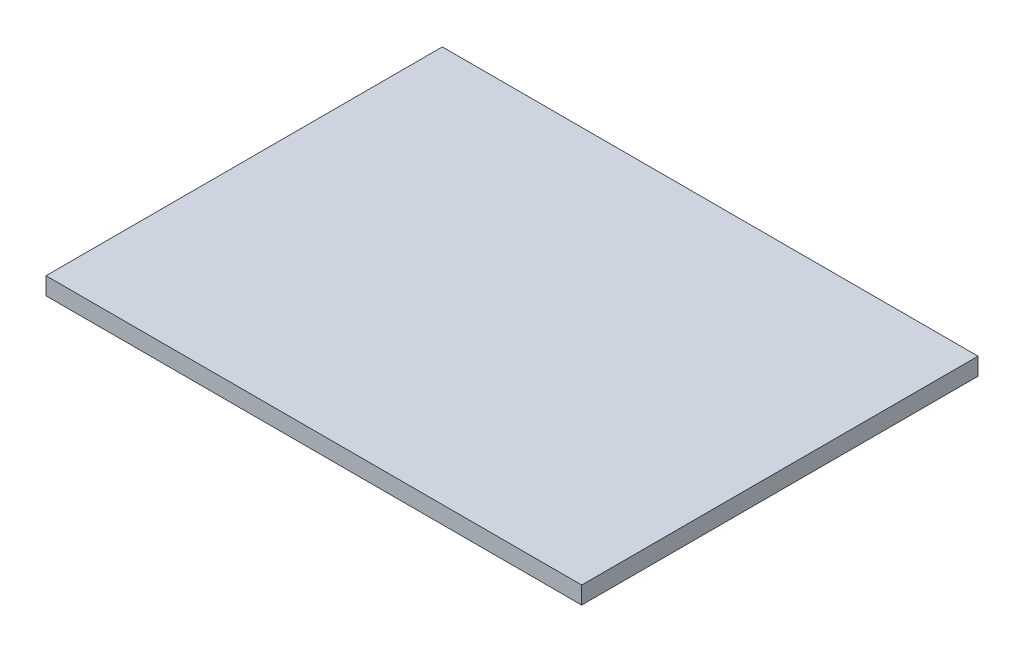
SolidWorks part; units mm, degrees
ref_plane "Front Plane" through (0, 0, 0) normal (0, 0, 1) x (1, 0, 0)
ref_plane "Top Plane" through (0, 0, 0) normal (0, 1, 0) x (1, 0, 0)
ref_plane "Right Plane" through (0, 0, 0) normal (1, 0, 0) x (0, 0, -1)
sketch "Sketch1" plane through (0, 0, 0) normal (0, 1, 0) x (1, 0, 0)
  line L1 (-97.6312, -72.2313) -> (97.6313, -72.2313)
  line L2 (-97.6312, -72.2313) -> (-97.6312, 72.2313)
  line L3 (-97.6312, 72.2313) -> (97.6313, 72.2313)
  line L4 (97.6313, -72.2313) -> (97.6313, 72.2313)
  line L5 (-97.6312, -72.2313) -> (97.6313, 72.2313) construction
  line L6 (-97.6312, 72.2313) -> (97.6313, -72.2313) construction
  point P0 (0, 0)
  dimension "D1" = 195.2625
  dimension "D2" = 144.4625
extrude "Boss-Extrude1" add sketch "Sketch1" along normal blind 6.35
sketch "Sketch2" [suppressed] plane through (0, 6.35, 0) normal (0, 1, 0) x (1, 0, 0)
  line L0 (-72.2313, 46.8312) -> (-72.2313, -46.8312) construction
  line L1 (-72.2313, 6.35) -> (-59.5312, 6.35)
  line L2 (-72.2313, 6.35) -> (-72.2313, -6.35)
  line L3 (-72.2313, -6.35) -> (-59.5312, -6.35)
  line L4 (-59.5312, 6.35) -> (-59.5312, -6.35)
  point P4 (-59.5312, 0)
  dimension "D1" = 12.7
  dimension "D2" = 12.7
extrude "Cut-Extrude1" [suppressed] cut sketch "Sketch2" against normal blind 6.35
fillet "Fillet3" [suppressed] radius 6.35
fillet "Fillet4" [suppressed] radius 6.35
